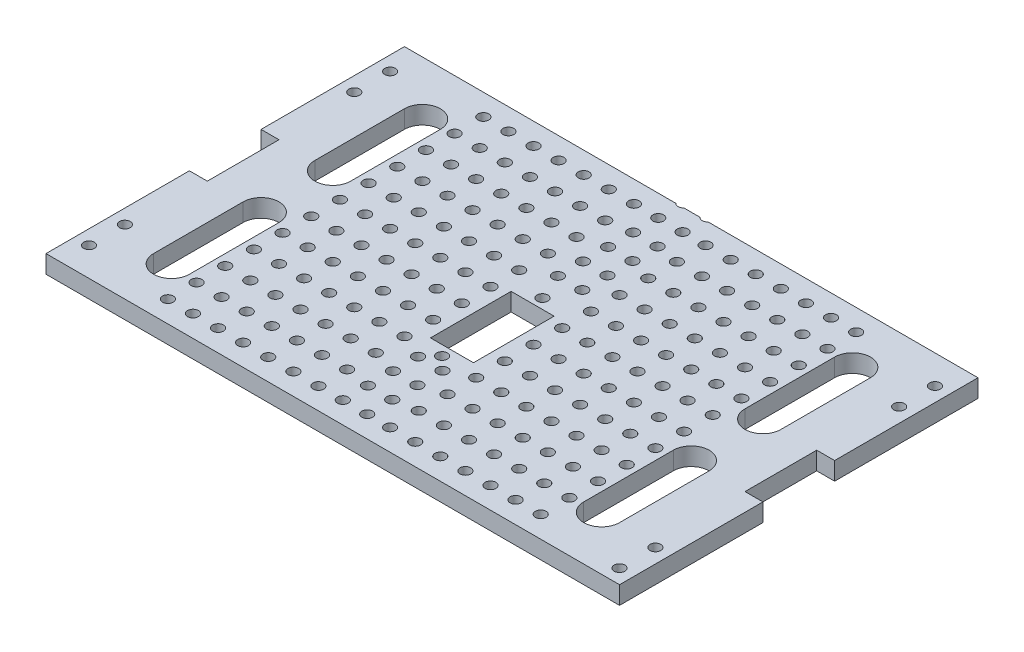
SolidWorks part; units mm, degrees
material "6063-T4"
ref_plane "Front Plane" through (0, 0, 0) normal (0, 0, 1) x (1, 0, 0)
ref_plane "Top Plane" through (0, 0, 0) normal (0, 1, 0) x (1, 0, 0)
ref_plane "Right Plane" through (0, 0, 0) normal (1, 0, 0) x (0, 0, -1)
sketch "Sketch1" plane through (0, 0, 0) normal (0, 1, 0) x (1, 0, 0)
  line L1 (-80, 50) -> (80, 50)
  line L2 (-80, 50) -> (-80, -50)
  line L3 (-80, -50) -> (80, -50)
  line L4 (80, 50) -> (80, -50)
  line L5 (-80, 50) -> (80, -50) construction
  line L6 (-80, -50) -> (80, 50) construction
  point P0 (0, 0)
  dimension "D1" = 160
  dimension "D2" = 100
extrude "Boss-Extrude1" add sketch "Sketch1" along normal blind 5
sketch "Sketch2" plane through (0, 5, 0) normal (0, 1, 0) x (1, 0, 0)
  circle A0 centre (0, 0) radius 3
  dimension "D1" = 6
extrude "Cut-Extrude1" cut sketch "Sketch2" against normal through all
sketch "Sketch12" plane through (0, 5, 0) normal (0, 1, 0) x (1, 0, 0)
  line L0 (-80, 50) -> (-80, -50) construction
  line L1 (-80, -10) -> (-75, -10)
  line L2 (-80, -10) -> (-80, 10)
  line L3 (-80, 10) -> (-75, 10)
  line L4 (-75, -10) -> (-75, 10)
  point P6 (-80, 0)
  point P7 (-80, 0)
  dimension "D1" = 20
  dimension "D2" = 5
extrude "Cut-Extrude9" cut sketch "Sketch12" against normal through all
mirror "Mirror6" about plane through (0, 0, 0) normal (1, 0, 0) of "Cut-Extrude9"
sketch "Sketch13" plane through (0, 5, 0) normal (0, 1, 0) x (1, 0, 0)
  line L0 (-6, -16.75) -> (-6, 5.75) construction
  line L1 (-6, -16.75) -> (-6, 5.75)
  line L2 (-6, -16.75) -> (6, -16.75)
  line L3 (6, -16.75) -> (6, 5.75)
  line L4 (6, 5.75) -> (-6, 5.75)
  line L8 (6, 6.25) -> (6, 10.25) construction
  circle A0 centre (0, 8.5) radius 1.5
  circle A1 centre (0, -19.5) radius 1.5
  dimension "D1" = 3
  dimension "D2" = 3
extrude "Cut-Extrude10" cut sketch "Sketch13" against normal through all
sketch "Sketch14" plane through (0, 5, 0) normal (0, 1, 0) x (1, 0, 0)
  circle A0 centre (-76, 42) radius 1.5
  circle A1 centre (-76, 32) radius 1.5
  circle A2 centre (-76, -42) radius 1.5
  circle A3 centre (-76, -32) radius 1.5
  circle A4 centre (76, -36) radius 1.5
  circle A5 centre (76, -46) radius 1.5
  circle A6 centre (76, 42) radius 1.5
  circle A7 centre (76, 32) radius 1.5
  dimension "D1" = 3
extrude "Cut-Extrude11" cut sketch "Sketch14" against normal through all
sketch "Sketch15" plane through (0, 5, 0) normal (0, 1, 0) x (1, 0, 0)
  line L0 (-60, 35) -> (-60, 10) construction
  line L1 (-55, 35) -> (-55, 10)
  line L2 (-65, 35) -> (-65, 10)
  line L3 (-60, -10) -> (-60, -35) construction
  line L4 (-55, -10) -> (-55, -35)
  line L5 (-65, -10) -> (-65, -35)
  line L6 (-80, 50) -> (-80, 10) construction
  line L7 (80, 50) -> (-80, 50) construction
  line L8 (-80, -50) -> (80, -50) construction
  arc A0 (-55, 35) -> (-65, 35) centre (-60, 35) ccw
  arc A1 (-65, 10) -> (-55, 10) centre (-60, 10) ccw
  arc A2 (-55, -10) -> (-65, -10) centre (-60, -10) ccw
  arc A3 (-65, -35) -> (-55, -35) centre (-60, -35) ccw
  point P2 (-60, 22.5)
  point P7 (-60, -22.5)
  dimension "D1" = 5
  dimension "D2" = 5
  dimension "D6" = 15
  dimension "D7" = 15
  dimension "D3" = 25
  dimension "D4" = 25
  dimension "D5" = 20
extrude "Cut-Extrude12" cut sketch "Sketch15" against normal blind 10
sketch "Sketch16" plane through (0, 5, 0) normal (0, 1, 0) x (1, 0, 0)
  line L0 (-6, 5.75) -> (-6, 50) construction
  line L1 (80, 50) -> (-80, 50) construction
  line L2 (-6, 44) -> (-80, 44) construction
  line L3 (-80, 50) -> (-80, 10) construction
  circle A0 centre (-52, 44) radius 1.5
  arc A1 (-55, 35) -> (-65, 35) centre (-60, 35) ccw construction
  circle A2 centre (-45, 44) radius 1.5
  circle A3 centre (-38, 44) radius 1.5
  circle A4 centre (-31, 44) radius 1.5
  circle A5 centre (-24, 44) radius 1.5
  circle A6 centre (-17, 44) radius 1.5
  circle A7 centre (-10, 44) radius 1.5
  dimension "D2" = 3
  dimension "D3" = 8
  dimension "D1" = 6
extrude "Cut-Extrude13" cut sketch "Sketch16" against normal through all
pattern_linear "LPattern1" count 12 spacing 8 along (0, 0, 1) of "Cut-Extrude13"
mirror "Mirror7" about plane through (0, 0, 0) normal (1, 0, 0) of "Cut-Extrude12", "Cut-Extrude13", "LPattern1"
sketch "Sketch17" plane through (0, 5, 0) normal (0, 1, 0) x (1, 0, 0)
  line L0 (-10, 44) -> (10, 44) construction
  circle A0 centre (-3.2, 44) radius 1.5
  circle A1 centre (3.6, 44) radius 1.5
  circle A2 centre (-10, 44) radius 1.5 construction
  dimension "D1" = 3
  dimension "D2" = 6.8
  dimension "D3" = 6.8
extrude "Cut-Extrude14" cut sketch "Sketch17" against normal through all
pattern_linear "LPattern2" count 5 spacing 7 along (0, 0, 1) of "Cut-Extrude14"
mirror "Mirror8" about plane through (0, 0, 0) normal (0, 0, 1) of "Cut-Extrude14"
pattern_linear "LPattern3" count 4 spacing 7 along (0, 0, -1) of "Mirror8", "Cut-Extrude14"
